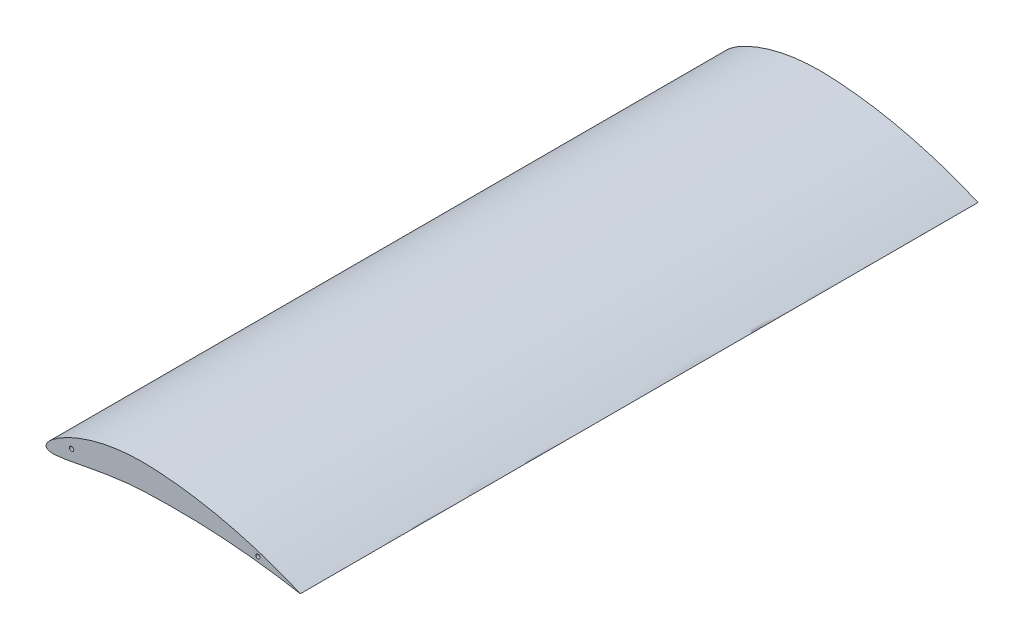
SolidWorks part; units mm, degrees
material "Thornel Mat VMA"
ref_plane "Front Plane" through (0, 0, 0) normal (0, 0, 1) x (1, 0, 0)
ref_plane "Top Plane" through (0, 0, 0) normal (0, 1, 0) x (1, 0, 0)
ref_plane "Right Plane" through (0, 0, 0) normal (1, 0, 0) x (0, 0, -1)
curve "Curve2"
  spline degree 3 poles (380.1728, 0.1686, 0) (381.2016, -0.0604, 0) (380.2163, 0.3141, 0) (379.4243, 0.6917, 0) (377.4514, 1.5124, 0) (375.004, 2.5552, 0) (371.7477, 3.9092, 0) (367.833, 5.5158, 0) (363.2199, 7.3703, 0) (357.9416, 9.4452, 0) (352.0084, 11.7151, 0) (345.4424, 14.1537, 0) (338.2645, 16.7309, 0) (330.4993, 19.4166, 0) (322.1733, 22.1778, 0) (313.316, 24.9843, 0) (303.9588, 27.8027, 0) (294.1353, 30.6015, 0) (283.8816, 33.3489, 0) (273.236, 36.0149, 0) (262.2385, 38.5692, 0) (250.9314, 40.985, 0) (239.3584, 43.2356, 0) (227.5652, 45.2972, 0) (215.5992, 47.1482, 0) (203.5087, 48.7693, 0) (191.3435, 50.143, 0) (179.1543, 51.2583, 0) (166.9924, 52.099, 0) (154.8171, 52.6816, 0) (142.6492, 52.9236, 0) (130.5443, 52.6134, 0) (118.6598, 51.8152, 0) (107.0796, 50.5408, 0) (95.863, 48.8273, 0) (85.066, 46.7119, 0) (74.742, 44.2412, 0) (64.9404, 41.4636, 0) (55.7072, 38.4324, 0) (47.0828, 35.206, 0) (39.1047, 31.8392, 0) (31.8043, 28.392, 0) (25.2087, 24.9209, 0) (19.3412, 21.4801, 0) (14.2186, 18.124, 0) (9.8549, 14.8989, 0) (6.2582, 11.8481, 0) (3.4316, 9.0076, 0) (1.3702, 6.4022, 0) (0.0666, 4.0394, 0) (-0.4776, 1.8821, 0) (-0.1412, -0.0637, 0) (1.0885, -1.6029, 0) (3.0387, -2.6395, 0) (5.6216, -3.2796, 0) (8.8577, -3.5728, 0) (12.7445, -3.5431, 0) (17.2698, -3.2105, 0) (22.4131, -2.5991, 0) (28.15, -1.7371, 0) (34.4535, -0.6553, 0) (41.2952, 0.6106, 0) (48.6458, 2.0245, 0) (56.4756, 3.5474, 0) (64.7545, 5.14, 0) (73.4534, 6.7604, 0) (82.5427, 8.3687, 0) (91.9937, 9.9235, 0) (101.7781, 11.3847, 0) (111.8681, 12.7128, 0) (122.2358, 13.8731, 0) (132.8534, 14.8249, 0) (143.7163, 15.5526, 0) (154.8882, 15.9766, 0) (166.3251, 16.271, 0) (177.964, 16.4881, 0) (189.6697, 16.5941, 0) (201.399, 16.5861, 0) (213.1085, 16.4571, 0) (224.754, 16.2044, 0) (236.2907, 15.8272, 0) (247.6739, 15.3294, 0) (258.8582, 14.7168, 0) (269.7991, 13.9969, 0) (280.4518, 13.181, 0) (290.7729, 12.2828, 0) (300.7188, 11.3158, 0) (310.2479, 10.2972, 0) (319.3194, 9.2439, 0) (327.894, 8.1745, 0) (335.9342, 7.1064, 0) (343.4047, 6.0586, 0) (350.2718, 5.0489, 0) (356.505, 4.0946, 0) (362.0736, 3.2109, 0) (366.9584, 2.4128, 0) (371.1183, 1.7173, 0) (374.5858, 1.1213, 0) (377.2045, 0.6756, 0) (379.3036, 0.2865, 0) (380.1728, 0.1686, 0) (381.2016, -0.0604, 0) (380.2163, 0.3141, 0) knots -0.004489 -0.002 -0.000501 0 0.0005 0.002 0.004491 0.007963 0.0124 0.017783 0.024086 0.031283 0.039342 0.048229 0.057904 0.068328 0.079457 0.091243 0.10364 0.116598 0.130063 0.143985 0.158306 0.172972 0.187927 0.203113 0.218472 0.233945 0.249473 0.264999 0.280462 0.295804 0.311324 0.326707 0.34181 0.356583 0.370972 0.384924 0.398387 0.411307 0.423633 0.435312 0.446295 0.456535 0.465988 0.474613 0.482377 0.489253 0.495224 0.500286 0.504461 0.507812 0.510481 0.512762 0.515043 0.517702 0.521013 0.525104 0.530021 0.535772 0.542341 0.549703 0.557819 0.566648 0.576147 0.586268 0.596965 0.60819 0.619899 0.632047 0.644592 0.657497 0.670724 0.68424 0.698011 0.712098 0.726728 0.741494 0.756341 0.771219 0.786073 0.800848 0.81549 0.829943 0.844153 0.858061 0.871615 0.884758 0.897436 0.909595 0.921182 0.932145 0.942437 0.952008 0.960816 0.968817 0.975974 0.98225 0.987616 0.992043 0.995511 0.998 0.999499 1 1.0005 1.002 1.004491 periodic
sketch "Sketch4" plane through (0, 0, 0) normal (0, 0, 1) x (1, 0, 0)
  spline S0 degree 3 poles (380.1728, 0.1686) (381.2016, -0.0604) (380.2163, 0.3141) (379.4243, 0.6917) (377.4514, 1.5124) (375.004, 2.5552) (371.7477, 3.9092) (367.833, 5.5158) (363.2199, 7.3703) (357.9416, 9.4452) (352.0084, 11.7151) (345.4424, 14.1537) (338.2645, 16.7309) (330.4993, 19.4166) (322.1733, 22.1778) (313.316, 24.9843) (303.9588, 27.8027) (294.1353, 30.6015) (283.8816, 33.3489) (273.236, 36.0149) (262.2385, 38.5692) (250.9314, 40.985) (239.3584, 43.2356) (227.5652, 45.2972) (215.5992, 47.1482) (203.5087, 48.7693) (191.3435, 50.143) (179.1543, 51.2583) (166.9924, 52.099) (154.8171, 52.6816) (142.6492, 52.9236) (130.5443, 52.6134) (118.6598, 51.8152) (107.0796, 50.5408) (95.863, 48.8273) (85.066, 46.7119) (74.742, 44.2412) (64.9404, 41.4636) (55.7072, 38.4324) (47.0828, 35.206) (39.1047, 31.8392) (31.8043, 28.392) (25.2087, 24.9209) (19.3412, 21.4801) (14.2186, 18.124) (9.8549, 14.8989) (6.2582, 11.8481) (3.4316, 9.0076) (1.3702, 6.4022) (0.0666, 4.0394) (-0.4776, 1.8821) (-0.1412, -0.0637) (1.0885, -1.6029) (3.0387, -2.6395) (5.6216, -3.2796) (8.8577, -3.5728) (12.7445, -3.5431) (17.2698, -3.2105) (22.4131, -2.5991) (28.15, -1.7371) (34.4535, -0.6553) (41.2952, 0.6106) (48.6458, 2.0245) (56.4756, 3.5474) (64.7545, 5.14) (73.4534, 6.7604) (82.5427, 8.3687) (91.9937, 9.9235) (101.7781, 11.3847) (111.8681, 12.7128) (122.2358, 13.8731) (132.8534, 14.8249) (143.7163, 15.5526) (154.8882, 15.9766) (166.3251, 16.271) (177.964, 16.4881) (189.6697, 16.5941) (201.399, 16.5861) (213.1085, 16.4571) (224.754, 16.2044) (236.2907, 15.8272) (247.6739, 15.3294) (258.8582, 14.7168) (269.7991, 13.9969) (280.4518, 13.181) (290.7729, 12.2828) (300.7188, 11.3158) (310.2479, 10.2972) (319.3194, 9.2439) (327.894, 8.1745) (335.9342, 7.1064) (343.4047, 6.0586) (350.2718, 5.0489) (356.505, 4.0946) (362.0736, 3.2109) (366.9584, 2.4128) (371.1183, 1.7173) (374.5858, 1.1213) (377.2045, 0.6756) (379.3036, 0.2865) (380.1728, 0.1686) (381.2016, -0.0604) (380.2163, 0.3141) knots -0.004489 -0.002 -0.000501 0 0.0005 0.002 0.004491 0.007963 0.0124 0.017783 0.024086 0.031283 0.039342 0.048229 0.057904 0.068328 0.079457 0.091243 0.10364 0.116598 0.130063 0.143985 0.158306 0.172972 0.187927 0.203113 0.218472 0.233945 0.249473 0.264999 0.280462 0.295804 0.311324 0.326707 0.34181 0.356583 0.370972 0.384924 0.398387 0.411307 0.423633 0.435312 0.446295 0.456535 0.465988 0.474613 0.482377 0.489253 0.495224 0.500286 0.504461 0.507812 0.510481 0.512762 0.515043 0.517702 0.521013 0.525104 0.530021 0.535772 0.542341 0.549703 0.557819 0.566648 0.576147 0.586268 0.596965 0.60819 0.619899 0.632047 0.644592 0.657497 0.670724 0.68424 0.698011 0.712098 0.726728 0.741494 0.756341 0.771219 0.786073 0.800848 0.81549 0.829943 0.844153 0.858061 0.871615 0.884758 0.897436 0.909595 0.921182 0.932145 0.942437 0.952008 0.960816 0.968817 0.975974 0.98225 0.987616 0.992043 0.995511 0.998 0.999499 1 1.0005 1.002 1.004491 only from (381, 0) to (381, 0) construction
  spline S1 degree 3 poles (380.1728, 0.1686) (381.2016, -0.0604) (380.2163, 0.3141) (379.4243, 0.6917) (377.4514, 1.5124) (375.004, 2.5552) (371.7477, 3.9092) (367.833, 5.5158) (363.2199, 7.3703) (357.9416, 9.4452) (352.0084, 11.7151) (345.4424, 14.1537) (338.2645, 16.7309) (330.4993, 19.4166) (322.1733, 22.1778) (313.316, 24.9843) (303.9588, 27.8027) (294.1353, 30.6015) (283.8816, 33.3489) (273.236, 36.0149) (262.2385, 38.5692) (250.9314, 40.985) (239.3584, 43.2356) (227.5652, 45.2972) (215.5992, 47.1482) (203.5087, 48.7693) (191.3435, 50.143) (179.1543, 51.2583) (166.9924, 52.099) (154.8171, 52.6816) (142.6492, 52.9236) (130.5443, 52.6134) (118.6598, 51.8152) (107.0796, 50.5408) (95.863, 48.8273) (85.066, 46.7119) (74.742, 44.2412) (64.9404, 41.4636) (55.7072, 38.4324) (47.0828, 35.206) (39.1047, 31.8392) (31.8043, 28.392) (25.2087, 24.9209) (19.3412, 21.4801) (14.2186, 18.124) (9.8549, 14.8989) (6.2582, 11.8481) (3.4316, 9.0076) (1.3702, 6.4022) (0.0666, 4.0394) (-0.4776, 1.8821) (-0.1412, -0.0637) (1.0885, -1.6029) (3.0387, -2.6395) (5.6216, -3.2796) (8.8577, -3.5728) (12.7445, -3.5431) (17.2698, -3.2105) (22.4131, -2.5991) (28.15, -1.7371) (34.4535, -0.6553) (41.2952, 0.6106) (48.6458, 2.0245) (56.4756, 3.5474) (64.7545, 5.14) (73.4534, 6.7604) (82.5427, 8.3687) (91.9937, 9.9235) (101.7781, 11.3847) (111.8681, 12.7128) (122.2358, 13.8731) (132.8534, 14.8249) (143.7163, 15.5526) (154.8882, 15.9766) (166.3251, 16.271) (177.964, 16.4881) (189.6697, 16.5941) (201.399, 16.5861) (213.1085, 16.4571) (224.754, 16.2044) (236.2907, 15.8272) (247.6739, 15.3294) (258.8582, 14.7168) (269.7991, 13.9969) (280.4518, 13.181) (290.7729, 12.2828) (300.7188, 11.3158) (310.2479, 10.2972) (319.3194, 9.2439) (327.894, 8.1745) (335.9342, 7.1064) (343.4047, 6.0586) (350.2718, 5.0489) (356.505, 4.0946) (362.0736, 3.2109) (366.9584, 2.4128) (371.1183, 1.7173) (374.5858, 1.1213) (377.2045, 0.6756) (379.3036, 0.2865) (380.1728, 0.1686) (381.2016, -0.0604) (380.2163, 0.3141) knots -0.004489 -0.002 -0.000501 0 0.0005 0.002 0.004491 0.007963 0.0124 0.017783 0.024086 0.031283 0.039342 0.048229 0.057904 0.068328 0.079457 0.091243 0.10364 0.116598 0.130063 0.143985 0.158306 0.172972 0.187927 0.203113 0.218472 0.233945 0.249473 0.264999 0.280462 0.295804 0.311324 0.326707 0.34181 0.356583 0.370972 0.384924 0.398387 0.411307 0.423633 0.435312 0.446295 0.456535 0.465988 0.474613 0.482377 0.489253 0.495224 0.500286 0.504461 0.507812 0.510481 0.512762 0.515043 0.517702 0.521013 0.525104 0.530021 0.535772 0.542341 0.549703 0.557819 0.566648 0.576147 0.586268 0.596965 0.60819 0.619899 0.632047 0.644592 0.657497 0.670724 0.68424 0.698011 0.712098 0.726728 0.741494 0.756341 0.771219 0.786073 0.800848 0.81549 0.829943 0.844153 0.858061 0.871615 0.884758 0.897436 0.909595 0.921182 0.932145 0.942437 0.952008 0.960816 0.968817 0.975974 0.98225 0.987616 0.992043 0.995511 0.998 0.999499 1 1.0005 1.002 1.004491 only from (381, 0) to (381, 0)
  dimension "D1" = 381
extrude "Boss-Extrude2" add sketch "Sketch4" along normal blind 1016
sketch "Sketch5" plane through (0, 0, 0) normal (0, 0, -1) x (-1, 0, 0)
  line L0 (-317.3398, 16.5855) -> (-37.9398, 16.5855) construction
  line L1 (-317.3398, 23.7034) -> (-317.3398, 9.4676) construction
  circle A0 centre (-37.9398, 16.5855) radius 3.175
  circle A1 centre (-317.3398, 16.5855) radius 3.175
  spline S0 degree 3 poles (-380.2163, 0.3141) (-381.2016, -0.0604) (-380.1728, 0.1686) (-379.3036, 0.2865) (-377.2045, 0.6756) (-374.5858, 1.1213) (-371.1183, 1.7173) (-366.9584, 2.4128) (-362.0736, 3.2109) (-356.505, 4.0946) (-350.2718, 5.0489) (-343.4047, 6.0586) (-335.9342, 7.1064) (-327.894, 8.1745) (-319.3194, 9.2439) (-310.2479, 10.2972) (-300.7188, 11.3158) (-290.7729, 12.2828) (-280.4518, 13.181) (-269.7991, 13.9969) (-258.8582, 14.7168) (-247.6739, 15.3294) (-236.2907, 15.8272) (-224.754, 16.2044) (-213.1085, 16.4571) (-201.399, 16.5861) (-189.6697, 16.5941) (-177.964, 16.4881) (-166.3251, 16.271) (-154.8882, 15.9766) (-143.7163, 15.5526) (-132.8534, 14.8249) (-122.2358, 13.8731) (-111.8681, 12.7128) (-101.7781, 11.3847) (-91.9937, 9.9235) (-82.5427, 8.3687) (-73.4534, 6.7604) (-64.7545, 5.14) (-56.4756, 3.5474) (-48.6458, 2.0245) (-41.2952, 0.6106) (-34.4535, -0.6553) (-28.15, -1.7371) (-22.4131, -2.5991) (-17.2698, -3.2105) (-12.7445, -3.5431) (-8.8577, -3.5728) (-5.6216, -3.2796) (-3.0387, -2.6395) (-1.0885, -1.6029) (0.1412, -0.0637) (0.4776, 1.8821) (-0.0666, 4.0394) (-1.3702, 6.4022) (-3.4316, 9.0076) (-6.2582, 11.8481) (-9.8549, 14.8989) (-14.2186, 18.124) (-19.3412, 21.4801) (-25.2087, 24.9209) (-31.8043, 28.392) (-39.1047, 31.8392) (-47.0828, 35.206) (-55.7072, 38.4324) (-64.9404, 41.4636) (-74.742, 44.2412) (-85.066, 46.7119) (-95.863, 48.8273) (-107.0796, 50.5408) (-118.6598, 51.8152) (-130.5443, 52.6134) (-142.6492, 52.9236) (-154.8171, 52.6816) (-166.9924, 52.099) (-179.1543, 51.2583) (-191.3435, 50.143) (-203.5087, 48.7693) (-215.5992, 47.1482) (-227.5652, 45.2972) (-239.3584, 43.2356) (-250.9314, 40.985) (-262.2385, 38.5692) (-273.236, 36.0149) (-283.8816, 33.3489) (-294.1353, 30.6015) (-303.9588, 27.8027) (-313.316, 24.9843) (-322.1733, 22.1778) (-330.4993, 19.4166) (-338.2645, 16.7309) (-345.4424, 14.1537) (-352.0084, 11.7151) (-357.9416, 9.4452) (-363.2199, 7.3703) (-367.833, 5.5158) (-371.7477, 3.9092) (-375.004, 2.5552) (-377.4514, 1.5124) (-379.4243, 0.6917) (-380.2163, 0.3141) (-381.2016, -0.0604) (-380.1728, 0.1686) knots -0.004491 -0.002 -0.0005 0 0.000501 0.002 0.004489 0.007957 0.012384 0.01775 0.024026 0.031183 0.039184 0.047992 0.057563 0.067855 0.078818 0.090405 0.102564 0.115242 0.128385 0.141939 0.155847 0.170057 0.18451 0.199152 0.213927 0.228781 0.243659 0.258506 0.273272 0.287902 0.301989 0.31576 0.329276 0.342503 0.355408 0.367953 0.380101 0.39181 0.403035 0.413732 0.423853 0.433352 0.442181 0.450297 0.457659 0.464228 0.469979 0.474896 0.478987 0.482298 0.484957 0.487238 0.489519 0.492188 0.495539 0.499714 0.504776 0.510747 0.517623 0.525387 0.534012 0.543465 0.553705 0.564688 0.576367 0.588693 0.601613 0.615076 0.629028 0.643417 0.65819 0.673293 0.688676 0.704196 0.719538 0.735001 0.750527 0.766055 0.781528 0.796887 0.812073 0.827028 0.841694 0.856015 0.869937 0.883402 0.89636 0.908757 0.920543 0.931672 0.942096 0.951771 0.960658 0.968717 0.975914 0.982217 0.9876 0.992037 0.995509 0.998 0.9995 1 1.000501 1.002 1.004489 only from (-381, 0) to (-381, 0) construction
  point P4 (-322.4117, 22.0793)
  point P6 (-317.3398, 16.5855)
  dimension "D1" = 6.35
  dimension "D2" = 6.35
  dimension "D3" = 279.4
extrude "Cut-Extrude1" cut sketch "Sketch5" against normal up to next
